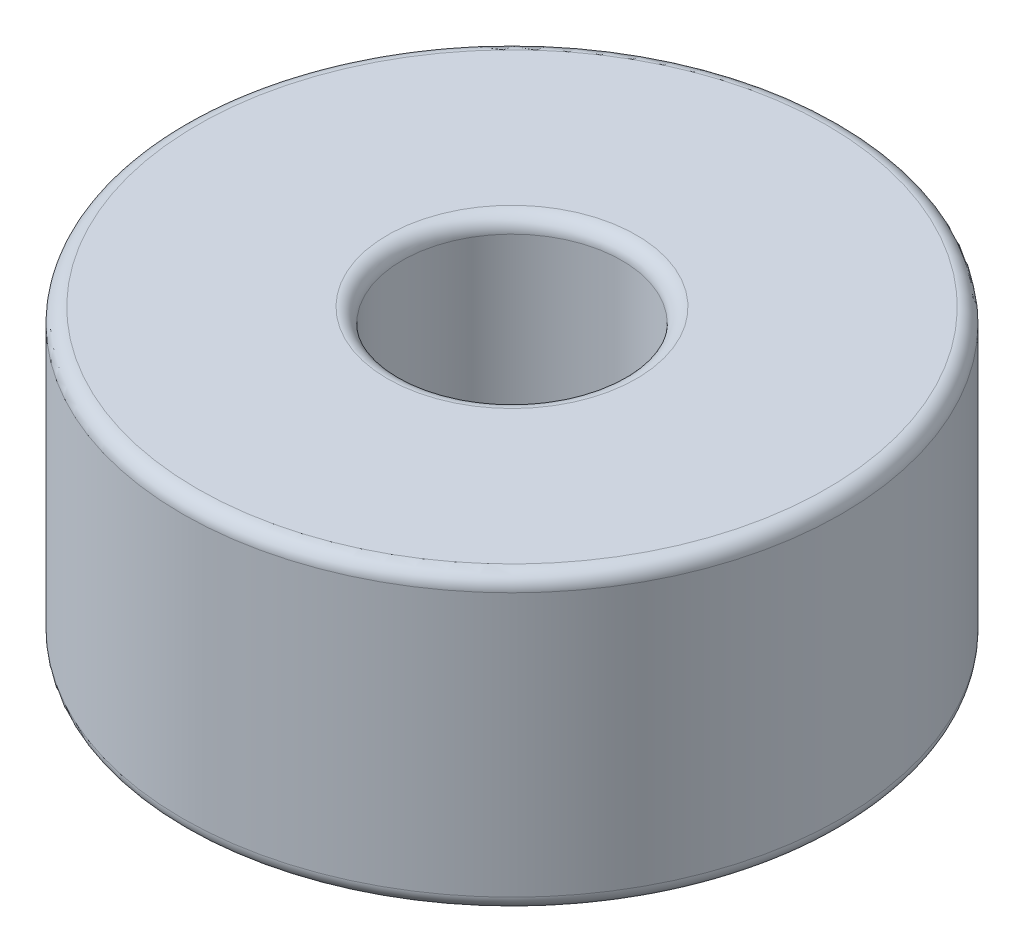
SolidWorks part; units mm, degrees
ref_plane "Front Plane" through (0, 0, 0) normal (0, 0, 1) x (1, 0, 0)
ref_plane "Top Plane" through (0, 0, 0) normal (0, 1, 0) x (1, 0, 0)
ref_plane "Right Plane" through (0, 0, 0) normal (1, 0, 0) x (0, 0, -1)
sketch "Sketch1" plane through (0, 0, 0) normal (0, 1, 0) x (1, 0, 0)
  circle A0 centre (0, 0) radius 45
  circle A1 centre (0, 0) radius 15
  dimension "D1" = 90
  dimension "D2" = 30
extrude "Boss-Extrude1" add sketch "Sketch1" along normal blind 40
fillet "Fillet1" radius 2 4 edges at (0, 0, 15) (0, 0, 45) (0, 40, 15) (0, 40, 45)
